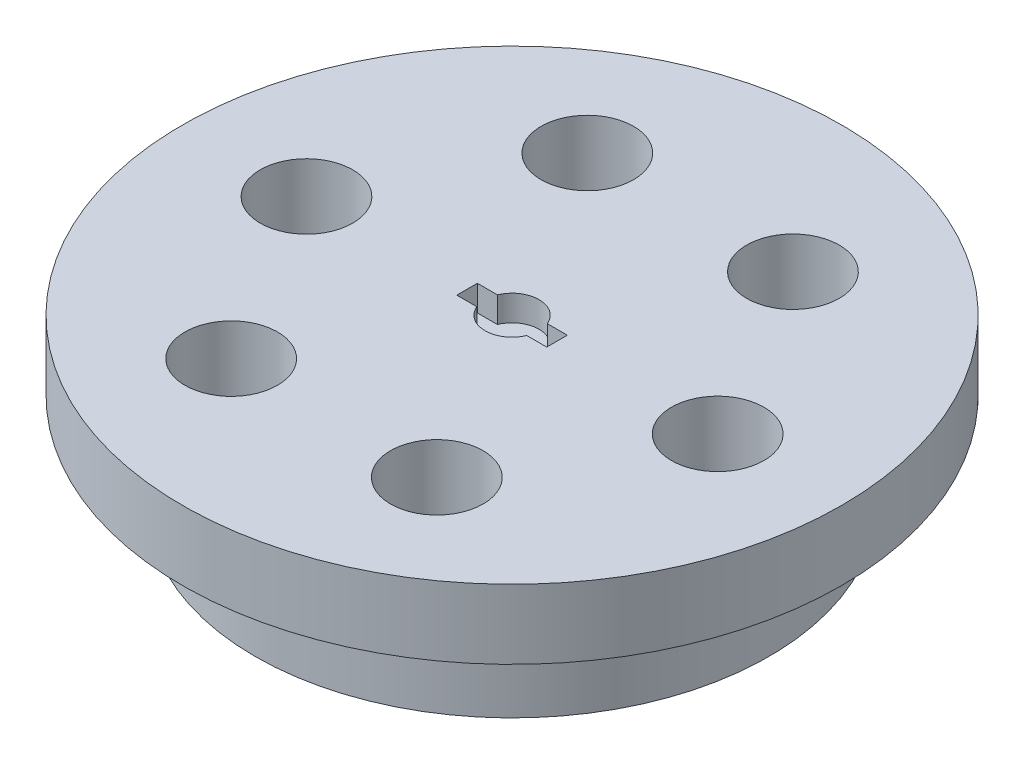
SolidWorks part; units mm, degrees
ref_plane "Front Plane" through (0, 0, 0) normal (0, 0, 1) x (1, 0, 0)
ref_plane "Top Plane" through (0, 0, 0) normal (0, 1, 0) x (1, 0, 0)
ref_plane "Right Plane" through (0, 0, 0) normal (1, 0, 0) x (0, 0, -1)
sketch "Sketch1" plane through (0, 60.4104, 0) normal (0, 1, 0) x (1, 0, 0)
  circle A0 centre (0, 0) radius 7.55
  circle A1 centre (0, 0) radius 20.0025
  circle A2 centre (-8, 13.8564) radius 2.25
  circle A3 centre (8, 13.8564) radius 2.25
  circle A4 centre (16, 0) radius 2.25
  circle A5 centre (8, -13.8564) radius 2.25
  circle A6 centre (-8, -13.8564) radius 2.25
  circle A7 centre (-16, 0) radius 2.25
  point P20 (0, 0)
  dimension "D1" = 6
extrude "Boss-Extrude1" add sketch "Sketch1" along normal blind 7.6
sketch "Sketch9" plane through (0, 65.4, 0) normal (0, 1, 0) x (1, 0, 0)
  circle A1 centre (0, 0) radius 6.9526
  circle A2 centre (0, 0) radius 7.55
extrude "Boss-Extrude5" add sketch "Sketch9" along normal up to surface (2.6104 mm away) up to face at (-8, 68.0104, 16.1064)
sketch "Sketch2" plane through (0, 68.0104, 0) normal (0, -1, 0) x (-1, 0, 0)
  line L0 (0, 0) -> (-16, 0) construction
  circle A7 centre (0, 0) radius 25.6464
  circle A8 centre (-16, 0) radius 3.6
  circle A9 centre (-8, 13.8564) radius 3.6
  circle A10 centre (8, 13.8564) radius 3.6
  circle A11 centre (16, 0) radius 3.6
  circle A12 centre (8, -13.8564) radius 3.6
  circle A13 centre (-8, -13.8564) radius 3.6
  point P17 (0, 0)
  point P18 (0, 0)
  dimension "D1" = 6
extrude "Boss-Extrude2" add sketch "Sketch2" against normal blind 5.4
sketch "Sketch4" plane through (0, 73.4104, 0) normal (0, -1, 0) x (1, 0, 0)
  circle A1 centre (0, 0) radius 6.9526
extrude "Cut-Extrude1" cut sketch "Sketch4" along normal blind 8
sketch "Sketch10" plane through (0, 73.4104, 0) normal (0, 1, 0) x (1, 0, 0)
  circle A1 centre (0, 0) radius 6.9526
extrude "Boss-Extrude6" add sketch "Sketch10" against normal up to surface (8.0104 mm away) up to face at (0, 65.4, 7.55)
sketch "Sketch11" plane through (0, 73.4104, 0) normal (0, 1, 0) x (1, 0, 0)
  line L0 (1.9416, 0.8) -> (3.5, 0.8)
  line L1 (-3.5, -0.8) -> (-1.9416, -0.8)
  line L2 (-3.5, -0.8) -> (-3.5, 0.8)
  line L3 (-3.5, 0.8) -> (-1.9416, 0.8)
  line L4 (3.5, -0.8) -> (3.5, 0.8)
  line L5 (-3.5, -0.8) -> (3.5, 0.8) construction
  line L6 (-3.5, 0.8) -> (3.5, -0.8) construction
  line L7 (1.9416, -0.8) -> (3.5, -0.8)
  arc A0 (-1.9416, -0.8) -> (1.9416, -0.8) centre (0, 0) ccw
  arc A1 (1.9416, 0.8) -> (-1.9416, 0.8) centre (0, 0) ccw
extrude "Cut-Extrude2" cut sketch "Sketch11" against normal blind 2
